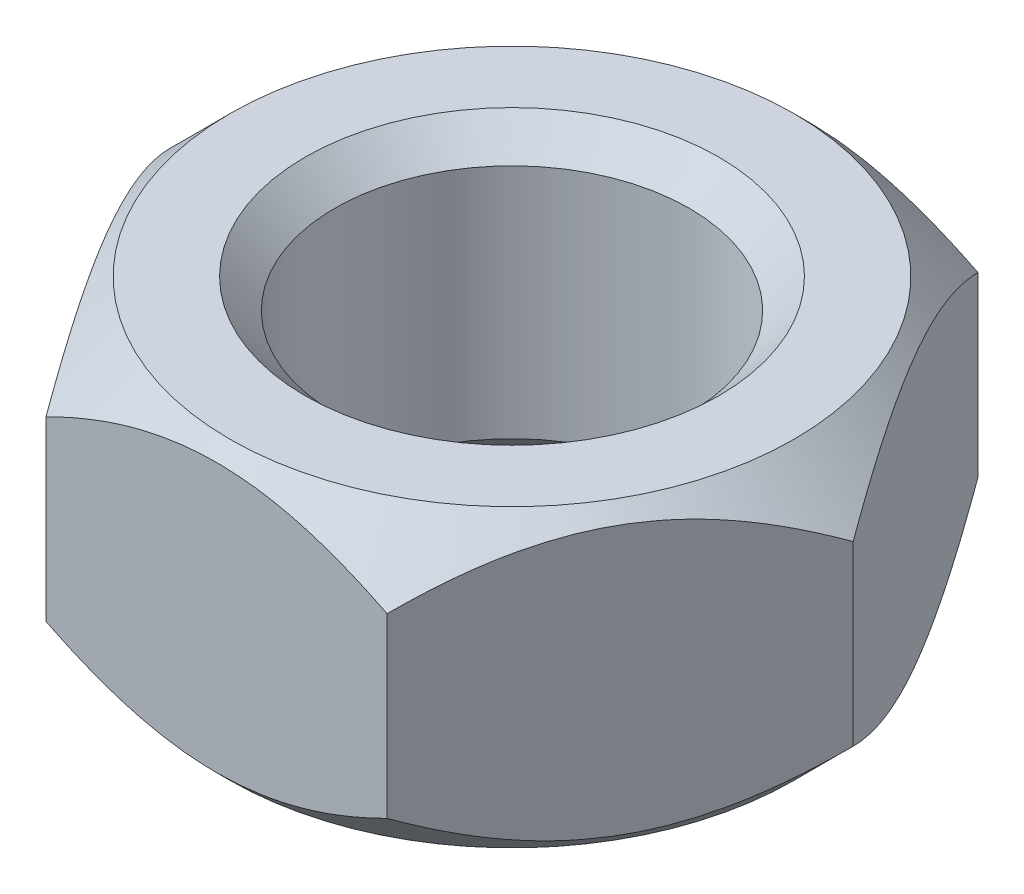
SolidWorks part; units mm, degrees
ref_plane "Спереди" through (0, 0, 0) normal (0, 0, 1) x (1, 0, 0)
ref_plane "Сверху" through (0, 0, 0) normal (0, 1, 0) x (1, 0, 0)
ref_plane "Справа" through (0, 0, 0) normal (1, 0, 0) x (0, 0, -1)
sketch "Эскиз1" plane through (0, 0, 0) normal (0, 1, 0) x (1, 0, 0)
  line L0 (-2.8868, 5) -> (2.8868, 5)
  line L1 (2.8868, 5) -> (5.7735, 0)
  line L2 (5.7735, 0) -> (2.8868, -5)
  line L3 (2.8868, -5) -> (-2.8868, -5)
  line L4 (-2.8868, -5) -> (-5.7735, 0)
  line L5 (-5.7735, 0) -> (-2.8868, 5)
  dimension "D5" = 5
  dimension "D2" = 120
  dimension "D3" = 120
  dimension "D4" = 120
  dimension "D6" = 5
  dimension "D7" = 5
  dimension "D8" = 5
  dimension "D9" = 5
  dimension "D10" = 120
  dimension "D11" = 5
extrude "Вытянуть1" add sketch "Эскиз1" against normal blind 5
sketch "Эскиз2" plane through (0, 0, 0) normal (0, 1, 0) x (-1, 0, 0)
  circle A0 centre (0, 0) radius 3
  dimension "D1" = 6
extrude "Вырез-Вытянуть1" cut sketch "Эскиз2" against normal through all
chamfer "Фаска1" distance 0.5 angle 45 2 edges at (0, -5, 3) (0, 0, 3)
ref_axis "Ось1" through (0, -0.5, 0) along (0, -1, 0)
ref_plane "Плоскость1" through (0, 0, 0) normal (0, 0, 1) x (1, 0, 0)
sketch "Эскиз3" plane through (0, 0, 0) normal (0, 0, 1) x (1, 0, 0)
  line L0 (-5.7735, -1) -> (-4.7735, 0)
  line L1 (-5.7735, -5) -> (-5.7735, 0) construction
  line L2 (-5.7735, 0) -> (-2.8868, 0) construction
  line L3 (-4.7735, 0) -> (-5.7735, 0)
  line L4 (-5.7735, 0) -> (-5.7735, -1)
  line L5 (-5.7735, -4) -> (-4.7735, -5)
  line L6 (-5.7735, -5) -> (-2.8868, -5) construction
  line L7 (-4.7735, -5) -> (-5.7735, -5)
  line L8 (-5.7735, -5) -> (-5.7735, -4)
  dimension "D1" = 1
  dimension "D2" = 1
  dimension "D3" = 1
  dimension "D4" = 1
revolve "Вырез-Повернуть1" cut sketch "Эскиз3" angle 360 about axis through (0, -0.5, 0) along (0, -1, 0)
